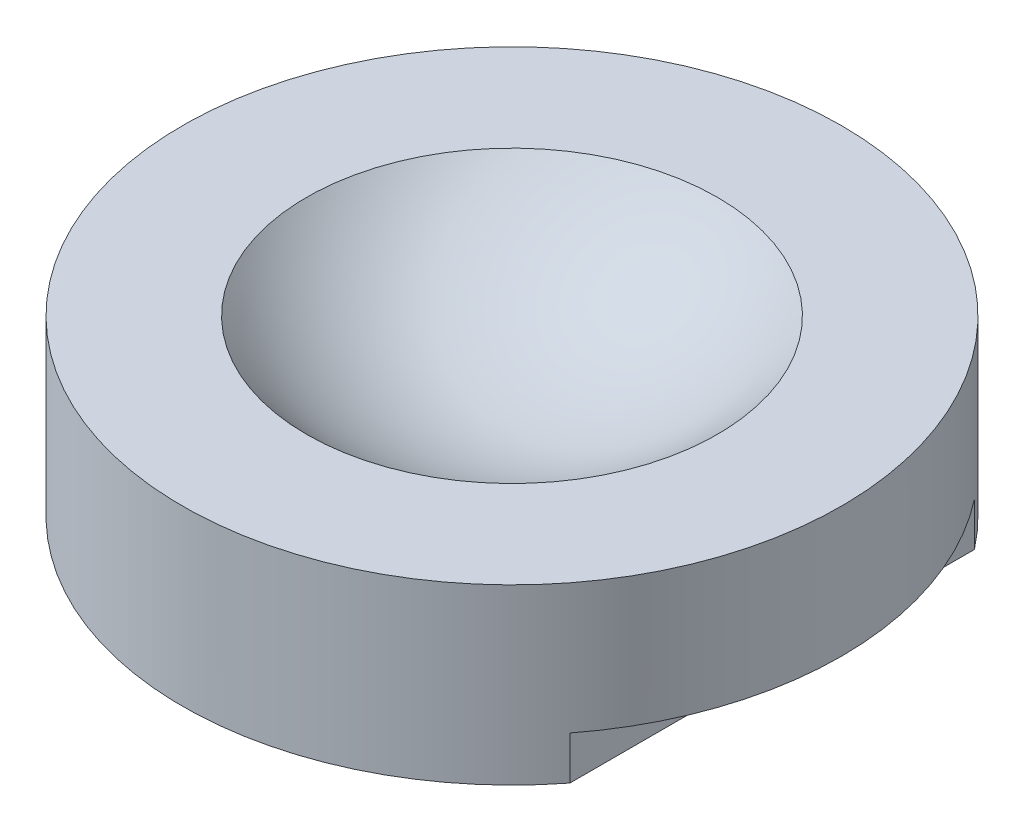
SolidWorks part; units mm, degrees
other "Fixed Steel Cup Liner 1"
other "Fixed Steel Cup Liner 1 Left"
ref_plane "Front Plane" through (0, 0, 0) normal (0, 0, 1) x (1, 0, 0)
ref_plane "Top Plane" through (0, 0, 0) normal (0, 1, 0) x (1, 0, 0)
ref_plane "Right Plane" through (0, 0, 0) normal (1, 0, 0) x (0, 0, -1)
sketch3d "Keyed Back Sketch datum points"
  point P0 (-56.2917, -69, 0)
  point P1 (-46.2917, -69, 0)
  point P2 (-56.2917, -69, 10)
ref_plane "Keyed Back Sketch plane" through (0, -69, 0) normal (0, -1, 0) x (-1, 0, 0)
sketch "Keyed Back Sketch" plane through (0, -69, 0) normal (0, -1, 0) x (-1, 0, 0)
  line L0 (23.2917, 2.3324) -> (23.2917, -2.3324)
  arc A0 (23.2917, -2.3324) -> (23.2917, 2.3324) centre (26.2917, 0) ccw
extrude "Keyed Back" add sketch "Keyed Back Sketch" along normal blind 0.5 separate body
sketch3d "Cup Blank Sketch datum points"
  point P0 (-56.2917, -69.5, 0)
  point P1 (-46.2917, -69.5, 0)
  point P2 (-56.2917, -69.5, 10)
ref_plane "Cup Blank Sketch plane" through (0, -69.5, 0) normal (0, -1, 0) x (-1, 0, 0)
sketch "Cup Blank Sketch" plane through (0, -69.5, 0) normal (0, -1, 0) x (-1, 0, 0)
  circle A0 centre (26.2917, 0) radius 3.8
extrude "Cup Blank" add sketch "Cup Blank Sketch" along normal blind 1.5
sketch3d "Spherical Bearing Seat axis line"
  line L0 (-26.2917, -73, -10) -> (-26.2917, -73, 10) construction
ref_axis "Spherical Bearing Seat axis" through (-26.2917, -73, -10) along (0, 0, 1)
sketch3d "Spherical Bearing Seat profile datum points"
  point P0 (-26.2917, -73, 0)
  point P1 (-16.2917, -73, 0)
  point P2 (-26.2917, -73, 10)
ref_plane "Spherical Bearing Seat profile plane" through (0, -73, 0) normal (0, -1, 0) x (-1, 0, 0)
sketch "Spherical Bearing Seat profile" plane through (0, -73, 0) normal (0, -1, 0) x (-1, 0, 0)
  line L0 (26.2917, -3.1) -> (26.2917, 3.1)
  arc A0 (26.2917, 3.1) -> (26.2917, -3.1) centre (26.2917, 0) ccw
revolve "Spherical Bearing Seat" cut sketch "Spherical Bearing Seat profile" angle 360 about axis through (-26.2917, -73, -10) along (0, 0, 1)
sketch3d "Mirror1 profile datum points"
  point P0 (0, 0, 0)
  point P1 (10, 0, 0)
  point P2 (0, 0, 10)
ref_plane "Mirror1 profile plane" through (0, 0, 0) normal (0, -1, 0) x (-1, 0, 0)
mirror "Mirror1" about plane through (0, 0, 0) normal (0, -1, 0) of bodies 103
delete or keep bodies "Remove1" type delete bodies bodies 103
